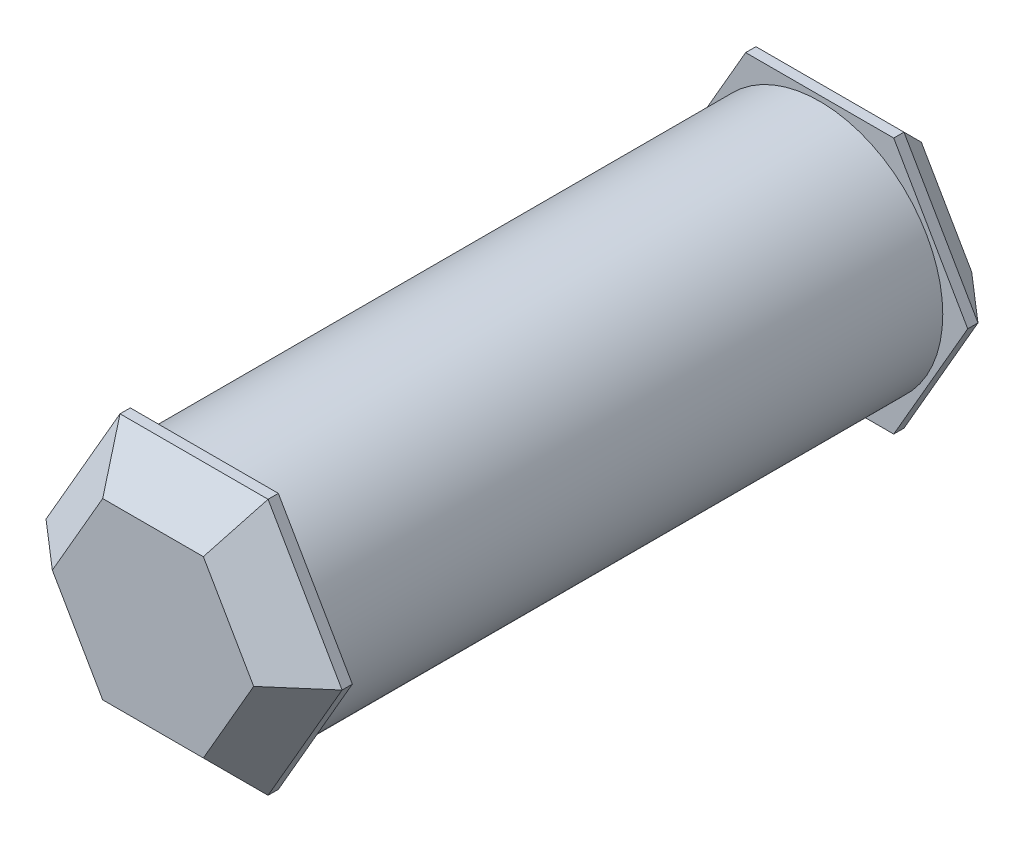
SolidWorks part; units mm, degrees
material "ABS"
ref_plane "Alzado" through (0, 0, 0) normal (0, 0, 1) x (1, 0, 0)
ref_plane "Planta" through (0, 0, 0) normal (0, 1, 0) x (1, 0, 0)
ref_plane "Vista lateral" through (0, 0, 0) normal (1, 0, 0) x (0, 0, -1)
sketch "Croquis1" plane through (0, 0, 0) normal (0, 0, 1) x (1, 0, 0)
  circle A0 centre (0, 0) radius 1.2
  dimension "D1" = 2.4
extrude "Saliente-Extruir1" add sketch "Croquis1" along normal blind 6
sketch "Croquis2" plane through (0, 0, 6) normal (0, 0, 1) x (1, 0, 0)
  line L1 (1.4434, 0) -> (0.7217, 1.25)
  line L2 (0.7217, 1.25) -> (-0.7217, 1.25)
  line L3 (-0.7217, 1.25) -> (-1.4434, 0)
  line L4 (-1.4434, 0) -> (-0.7217, -1.25)
  line L5 (-0.7217, -1.25) -> (0.7217, -1.25)
  line L6 (0.7217, -1.25) -> (1.4434, 0)
  circle A0 centre (0, 0) radius 1.25 construction
extrude "Saliente-Extruir2" add sketch "Croquis2" along normal blind 0.5
sketch "Croquis3" plane through (0, 0, 0) normal (0, 0, -1) x (-1, 0, 0)
  line L1 (1.4434, 0) -> (0.7217, 1.25)
  line L2 (0.7217, 1.25) -> (-0.7217, 1.25)
  line L3 (-0.7217, 1.25) -> (-1.4434, 0)
  line L4 (-1.4434, 0) -> (-0.7217, -1.25)
  line L5 (-0.7217, -1.25) -> (0.7217, -1.25)
  line L6 (0.7217, -1.25) -> (1.4434, 0)
  circle A0 centre (0, 0) radius 1.25 construction
extrude "Saliente-Extruir3" add sketch "Croquis3" along normal blind 0.5
chamfer "Chaflán1" distance 0.4 angle 45 1 edges at (0, 1.25, 6.5)
chamfer "Chaflán2" distance 0.4 angle 45 1 edges at (1.198, 0.425, 6.5)
chamfer "Chaflán3" distance 0.4 angle 45 1 edges at (0.9671, -0.825, 6.5)
chamfer "Chaflán4" distance 0.4 angle 45 1 edges at (-0.2309, -1.25, 6.5)
chamfer "Chaflán5" distance 0.4 angle 45 1 edges at (-1.198, -0.425, 6.5)
chamfer "Chaflán6" distance 0.4 angle 45 1 edges at (-1.0825, 0.625, 6.5)
chamfer "Chaflán7" distance 0.4 angle 45 1 edges at (1.0825, -0.625, -0.5)
chamfer "Chaflán8" distance 0.4 angle 45 1 edges at (0.9671, 0.825, -0.5)
chamfer "Chaflán9" distance 0.4 angle 45 1 edges at (-0.2309, 1.25, -0.5)
chamfer "Chaflán10" distance 0.4 angle 45 1 edges at (-0.2309, -1.25, -0.5)
chamfer "Chaflán11" distance 0.4 angle 45 1 edges at (-1.198, -0.425, -0.5)
chamfer "Chaflán12" distance 0.4 angle 45 1 edges at (-1.0825, 0.625, -0.5)
